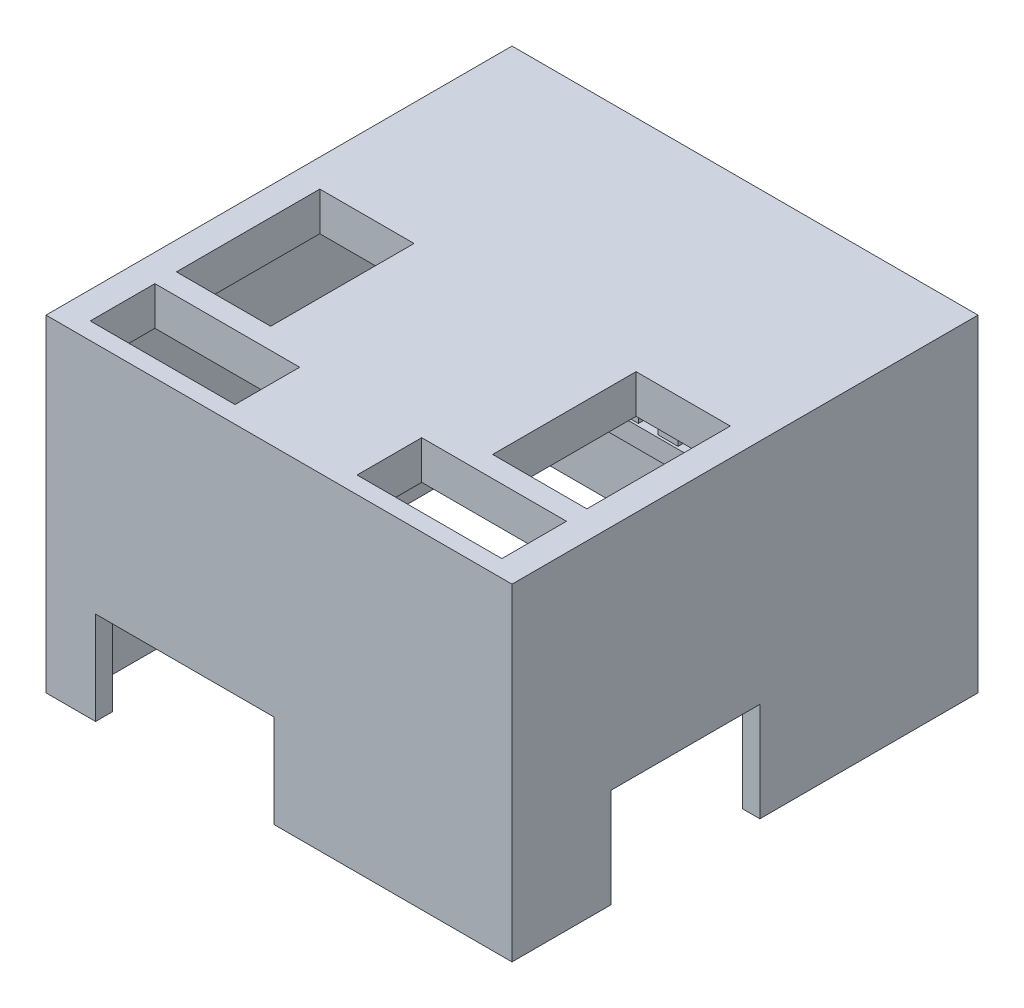
SolidWorks part; units mm, degrees
ref_plane "Front Plane" through (0, 0, 0) normal (0, 0, 1) x (1, 0, 0)
ref_plane "Top Plane" through (0, 0, 0) normal (0, 1, 0) x (1, 0, 0)
ref_plane "Right Plane" through (0, 0, 0) normal (1, 0, 0) x (0, 0, -1)
sketch "Sketch1" plane through (0, 0, 0) normal (0, 1, 0) x (1, 0, 0)
  line L1 (-23.5, -23.5) -> (23.5, -23.5)
  line L2 (-23.5, -23.5) -> (-23.5, 23.5)
  line L3 (-23.5, 23.5) -> (23.5, 23.5)
  line L4 (23.5, -23.5) -> (23.5, 23.5)
  line L5 (-23.5, -23.5) -> (23.5, 23.5) construction
  line L6 (-23.5, 23.5) -> (23.5, -23.5) construction
  point P0 (0, 0)
  dimension "D1" = 47
  dimension "D2" = 47
extrude "Boss-Extrude1" add sketch "Sketch1" along normal blind 30
sketch "Sketch2" plane through (0, 0, 0) normal (0, -1, 0) x (1, 0, 0)
  line L1 (-21.75, -21.75) -> (21.75, -21.75)
  line L2 (-21.75, -21.75) -> (-21.75, 21.75)
  line L3 (-21.75, 21.75) -> (21.75, 21.75)
  line L4 (21.75, -21.75) -> (21.75, 21.75)
  line L5 (-21.75, -21.75) -> (21.75, 21.75) construction
  line L6 (-21.75, 21.75) -> (21.75, -21.75) construction
  point P0 (0, 0)
  dimension "D1" = 43.5
  dimension "D2" = 43.5
extrude "Cut-Extrude1" cut sketch "Sketch2" against normal blind 26.1
sketch "Sketch4" plane through (0, 0, -23.5) normal (0, 0, -1) x (-1, 0, 0)
  line L0 (0, 30) -> (0, 0) construction
  line L1 (-23.5, 30) -> (23.5, 30) construction
  line L121 (15, 3.1573) -> (15, 23.1573)
  line L125 (-15, 3.1573) -> (-15, 23.1573)
  line L126 (-15, 13.1573) -> (-11, 13.1573) construction
  line L132 (-13, 3.1573) -> (-11, 3.1573)
  line L135 (-13, 23.1573) -> (-11, 23.1573)
  line L136 (-13, 23.1573) -> (-13, 3.1573)
  line L137 (-13, 3.1573) -> (-11, 3.1573)
  line L138 (-11, 23.1573) -> (-11, 3.1573)
  point P5 (0, 13.1573)
  dimension "D1" = 30
  dimension "D2" = 20
sketch "Sketch5" plane through (0, 0, 0) normal (0, -1, 0) x (1, 0, 0)
  line L0 (-23.5, 23.5) -> (23.5, 23.5)
  line L1 (23.5, 23.5) -> (23.5, -23.5)
  line L2 (23.5, 23.5) -> (23.5, -23.5) construction
  line L3 (23.5, -23.5) -> (-23.5, -23.5)
  line L4 (-23.5, -23.5) -> (-23.5, 23.5)
  line L6 (-16.6, 21.75) -> (-21.75, 21.75)
  line L7 (-21.75, 21.75) -> (-21.75, 16.6)
  line L8 (-21.75, 16.6) -> (-21.75, -16.6)
  line L9 (16.6, 21.75) -> (-16.6, 21.75)
  line L11 (21.75, 21.75) -> (21.75, 16.6)
  line L12 (16.6, 21.75) -> (21.75, 21.75)
  line L15 (16.6, -21.75) -> (21.75, -21.75)
  line L16 (21.75, -21.75) -> (21.75, -16.6)
  line L17 (16.6, -21.75) -> (-16.6, -21.75)
  line L18 (21.75, 16.6) -> (21.75, -16.6)
  line L19 (-21.75, -21.75) -> (-16.6, -21.75)
  line L20 (-21.75, -16.6) -> (-21.75, -21.75)
extrude "Boss-Extrude3" add sketch "Sketch5" along normal blind 3
extrude "Cut-Extrude3" cut sketch "Sketch4" against normal up to next contours L138 L135 L136 L132
pattern_linear "LPattern1" count 7 spacing 4 along (-1, 0, 0) of "Cut-Extrude3"
sketch "Sketch8" plane through (0, 0, -23.5) normal (0, 0, -1) x (-1, 0, 0)
  line L2 (-13, 23.1573) -> (-13, 3.1573) construction
  line L3 (-13, 21.1573) -> (13, 21.1573)
  line L4 (-13, 21.1573) -> (-13, 19.1573)
  line L6 (13, 21.1573) -> (13, 19.1573)
  line L7 (13, 23.1573) -> (13, 3.1573) construction
  line L8 (-13, 19.1573) -> (13, 19.1573)
  dimension "D1" = 2
extrude "Boss-Extrude4" add sketch "Sketch8" against normal blind 2
pattern_linear "LPattern2" count 5 spacing 4 along (0, -1, 0) of "Boss-Extrude4"
sketch "Sketch9" plane through (0, 0, 23.5) normal (0, 0, 1) x (1, 0, 0)
  line L0 (23.5, -3) -> (-23.5, -3) construction
  line L1 (-18.5, -3) -> (-0.5, -3)
  line L2 (-18.5, -3) -> (-18.5, 6.3899)
  line L3 (-18.5, 6.3899) -> (-0.5, 6.3899)
  line L4 (-0.5, -3) -> (-0.5, 6.3899)
  line L5 (-23.5, 30) -> (-23.5, -3) construction
  dimension "D1" = 5
  dimension "D2" = 23
extrude "Cut-Extrude4" cut sketch "Sketch9" against normal blind 10
sketch "Sketch10" plane through (-23.5, 0, 0) normal (-1, 0, 0) x (0, 0, 1)
  line L0 (23.5, -3) -> (-23.5, -3) construction
  line L1 (13.5, -3) -> (-1.5, -3)
  line L2 (13.5, -3) -> (13.5, 7)
  line L3 (13.5, 7) -> (-1.5, 7)
  line L4 (-1.5, -3) -> (-1.5, 7)
  line L5 (23.5, 30) -> (23.5, -3) construction
  dimension "D1" = 10
  dimension "D2" = 10
  dimension "D3" = 25
extrude "Cut-Extrude5" cut sketch "Sketch10" against normal through all from surface at 0 contours L2 L1 L4 L3 starting at face at (-23.5, 13.5, 0)
sketch "Sketch11" plane through (0, 30, 0) normal (0, 1, 0) x (1, 0, 0)
  line L0 (0, 0) -> (0, -8.1455) construction
  line L1 (-20.7005, 1.3179) -> (-11.1957, 1.3179)
  line L2 (-20.7005, 1.3179) -> (-20.7005, -13.1478)
  line L3 (-20.7005, -13.1478) -> (-11.1957, -13.1478)
  line L4 (-11.1957, 1.3179) -> (-11.1957, -13.1478)
  line L5 (-20.7571, -15.2597) -> (-6.1547, -15.2597)
  line L6 (-20.7571, -15.2597) -> (-20.7571, -21.7794)
  line L7 (-20.7571, -21.7794) -> (-6.1547, -21.7794)
  line L8 (-6.1547, -15.2597) -> (-6.1547, -21.7794)
  line L9 (20.7005, -13.1478) -> (11.1957, -13.1478)
  line L10 (11.1957, 1.3179) -> (11.1957, -13.1478)
  line L11 (20.7005, 1.3179) -> (11.1957, 1.3179)
  line L12 (20.7005, 1.3179) -> (20.7005, -13.1478)
  line L13 (20.7571, -21.7794) -> (6.1547, -21.7794)
  line L14 (6.1547, -15.2597) -> (6.1547, -21.7794)
  line L15 (20.7571, -15.2597) -> (6.1547, -15.2597)
  line L16 (20.7571, -15.2597) -> (20.7571, -21.7794)
extrude "Cut-Extrude6" cut sketch "Sketch11" against normal through all
